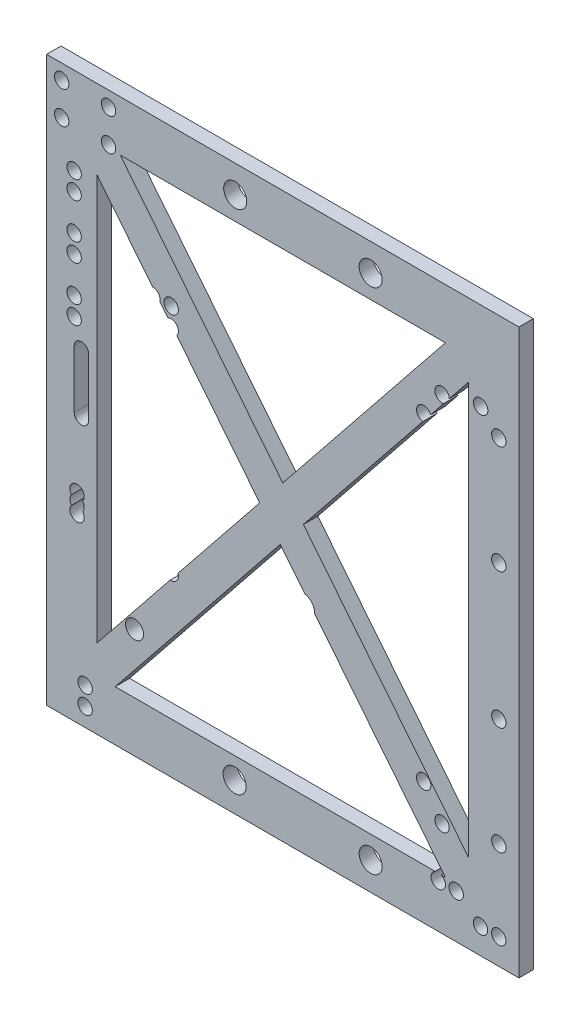
SolidWorks part; units mm, degrees
ref_plane "Front Plane" through (0, 0, 0) normal (0, 0, 1) x (1, 0, 0)
ref_plane "Top Plane" through (0, 0, 0) normal (0, 1, 0) x (1, 0, 0)
ref_plane "Right Plane" through (0, 0, 0) normal (1, 0, 0) x (0, 0, -1)
sketch "Sketch3" plane through (0, 0, 0) normal (0, 0, 1) x (1, 0, 0)
  line L0 (-58.532, 67.237) -> (-58.532, 10.995)
  line L1 (-65.532, 78.232) -> (0, 78.232)
  line L2 (-65.532, 78.232) -> (-65.532, 0)
  line L3 (-65.532, 0) -> (0, 0)
  line L4 (0, 78.232) -> (0, 0)
  line L5 (-56.0191, 7) -> (-10.2051, 7)
  line L6 (-7, 68.0998) -> (-7, 10.995)
  line L8 (-59.706, 45.116) -> (-59.706, 37.116)
  line L9 (-58.532, 71.232) -> (-7, 7) construction
  line L10 (-7, 71.232) -> (-58.532, 7) construction
  line L11 (-55.3269, 71.232) -> (-32.766, 43.111)
  line L12 (-58.532, 67.237) -> (-35.9711, 39.116)
  line L13 (-56.0191, 7) -> (-33.1121, 35.5524)
  line L14 (-58.532, 10.995) -> (-35.9711, 39.116)
  line L15 (-58.532, 71.232) -> (-58.532, 7) construction
  line L16 (-58.532, 7) -> (-7, 7) construction
  line L17 (-33.1121, 35.5524) -> (-10.2051, 7)
  line L18 (-32.766, 43.111) -> (-10.2051, 71.232)
  line L19 (-29.907, 39.5474) -> (-7, 10.995)
  line L20 (-29.907, 39.5474) -> (-7, 68.0998)
  line L21 (-58.532, 71.232) -> (-7, 71.232) construction
  line L22 (-55.3269, 71.232) -> (-10.2051, 71.232)
  line L23 (-7, 71.232) -> (-7, 7) construction
  line L25 (-61.706, 37.116) -> (-61.706, 45.116)
  circle A0 centre (-61.722, 66.169) radius 1
  circle A1 centre (-61.722, 63.629) radius 1
  circle A2 centre (-61.722, 58.669) radius 1
  circle A3 centre (-61.722, 56.129) radius 1
  circle A4 centre (-61.722, 51.169) radius 1
  circle A6 centre (-63.448, 76.164) radius 1
  circle A7 centre (-63.448, 71.664) radius 1
  circle A8 centre (-56.948, 71.664) radius 1
  circle A9 centre (-56.948, 76.164) radius 1
  circle A10 centre (-39.37, 74.422) radius 1.6
  circle A11 centre (-20.574, 74.422) radius 1.6
  circle A12 centre (-5.3091, 66.04) radius 1
  circle A13 centre (-2.794, 63.504) radius 1
  circle A14 centre (-2.794, 48.514) radius 1
  circle A15 centre (-2.794, 29.718) radius 1
  circle A16 centre (-2.794, 14.728) radius 1
  circle A17 centre (-2.799, 3.556) radius 1
  circle A18 centre (-5.339, 3.556) radius 1
  circle A19 centre (-8.7009, 6.096) radius 1
  circle A20 centre (-11.2009, 6.096) radius 1
  circle A21 centre (-20.574, 3.8909) radius 1.6
  circle A22 centre (-39.4509, 4.064) radius 1.6
  circle A23 centre (-60.198, 5.075) radius 1
  circle A24 centre (-60.198, 2.535) radius 1
  circle A25 centre (-61.32, 25.146) radius 1
  circle A26 centre (-61.32, 26.416) radius 1
  circle A27 centre (-61.32, 27.686) radius 1
  arc A28 (-61.706, 37.116) -> (-59.706, 37.116) centre (-60.706, 37.116) ccw
  arc A32 (-59.706, 45.116) -> (-61.706, 45.116) centre (-60.706, 45.116) ccw
  circle A33 centre (-61.722, 48.629) radius 1
  circle A34 centre (-48.255, 56.627) radius 1
  circle A35 centre (-13.213, 17.018) radius 1
  circle A36 centre (-10.668, 13.208) radius 1
  circle A37 centre (-48.26, 24.628) radius 1
  arc A39 (-47.4775, 53.4581) -> (-48.7004, 54.9823) centre (-48.255, 54.087) ccw
  arc A40 (-49.825, 56.3841) -> (-50.8218, 57.6266) centre (-50.795, 56.627) ccw
  circle A41 centre (-13.203, 61.214) radius 1
  circle A42 centre (-10.668, 64.77) radius 1
  circle A43 centre (-29.959, 29.718) radius 1.6
  circle A44 centre (-53.34, 15.24) radius 1.25
  dimension "D2" = 2
  dimension "D3" = 3.2
  dimension "D8" = 2.5
  dimension "D9" = 2
  dimension "D1" = 7
  dimension "D4" = 2.5
  dimension "D5" = 2.5
  dimension "D6" = 2.5
extrude "Boss-Extrude10" add sketch "Sketch3" along normal blind 2 contours L4 L1 L2 L3 A44 A43 L17 L5 A20 L13 A42 L20 L6 L19 A41 A40 L12 A39 L14 A37 L0 A36 A35 A34 A33 A32 L8 A28 L25 A27 A26 A25
sketch3d "3DSketch1"
  line L0 (0, 0, 2) -> (0, 0, 0) construction
  line L2 (-20.574, 0, 0) -> (-20.574, 0, 2)
  line L3 (-65.532, 0, 0) -> (0, 0, 0) construction
  line L4 (-65.532, 0, 2) -> (0, 0, 2) construction
  dimension "D1" = 20.574
ref_plane "Plane1" through (0, 39.116, 0) normal (0, 1, 0) x (1, 0, 0)
sketch "Sketch5" plane through (0, 0, 0) normal (0, -1, 0) x (1, 0, 0)
  line L0 (-20.574, 2) -> (-20.574, 0)
  line L1 (-39.454, 2) -> (-39.454, 0)
  line L2 (-65.532, 2) -> (0, 2) construction
  line L3 (36.0426, 0) -> (-36.0426, 0) construction
  line L4 (-39.454, 1) -> (-20.574, 1) construction
  line L9 (-26.2023, 4.5) -> (-27.6082, 6.935)
  line L10 (-27.6082, 6.935) -> (-30.4198, 6.935)
  line L11 (-33.014, 1.9998) -> (-25.014, 1.9998)
  line L12 (-30.014, 2) -> (-30.014, 7) construction
  line L13 (-25.014, 1.9998) -> (-25.014, 4.5)
  line L14 (-33.014, 1.9998) -> (-33.014, 4.5)
  line L15 (-25.014, 1.9998) -> (-25.014, 4.5)
  line L16 (-33.014, 1.9998) -> (-33.014, 4.5)
  line L17 (-30.4198, 6.935) -> (-31.8257, 4.5)
  line L18 (-31.8257, 4.5) -> (-30.4198, 2.065)
  line L19 (-30.4198, 2.065) -> (-27.6082, 2.065)
  line L20 (-27.6082, 2.065) -> (-26.2023, 4.5)
  arc A2 (-33.014, 4.5) -> (-25.014, 4.5) centre (-29.014, 4.5) cw
  circle A3 centre (-29.014, 4.5) radius 2.435 construction
  dimension "D2" = 8
  dimension "D3" = 2.5
  dimension "D4" = 4.87
  dimension "D1" = 18.88
